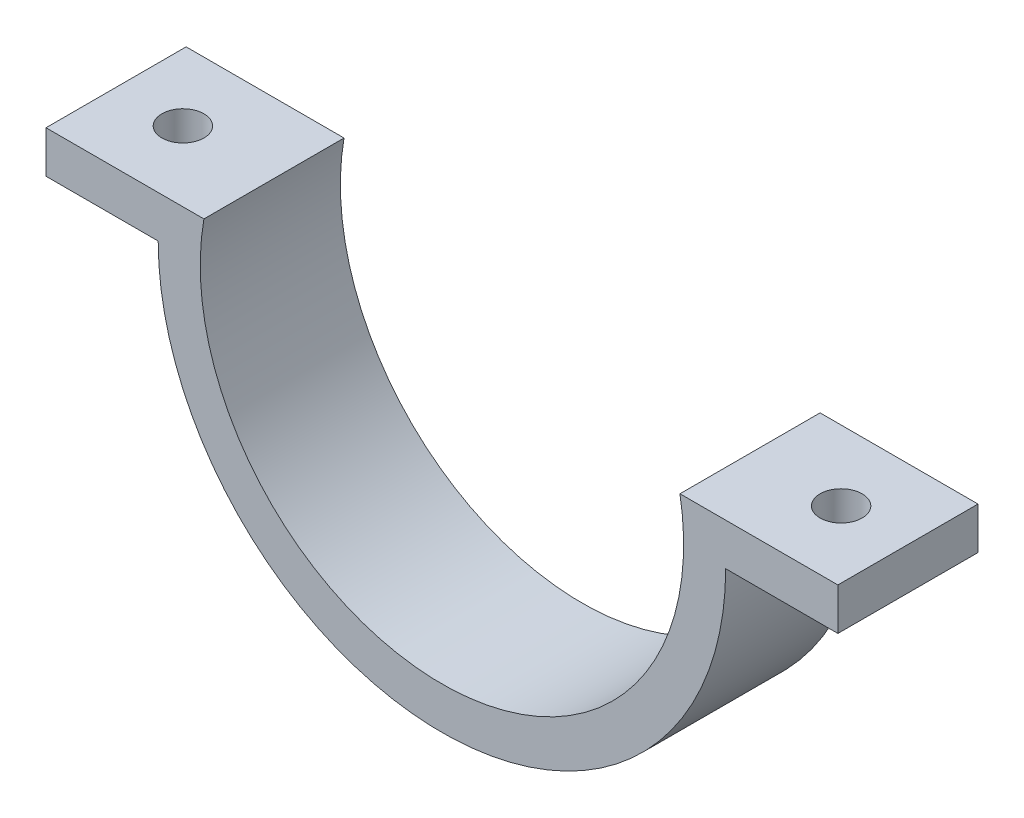
SolidWorks part; units mm, degrees
ref_plane "Front Plane" through (0, 0, 0) normal (0, 0, 1) x (1, 0, 0)
ref_plane "Top Plane" through (0, 0, 0) normal (0, 1, 0) x (1, 0, 0)
ref_plane "Right Plane" through (0, 0, 0) normal (1, 0, 0) x (0, 0, -1)
sketch "Sketch1" plane through (0, 0, 0) normal (0, 0, 1) x (1, 0, 0)
  line L0 (0, 0) -> (0, 3) construction
  line L1 (16.9871, 3) -> (-16.9871, 3) construction
  line L2 (-16.9871, 3) -> (-26.9871, 3)
  line L3 (16.9871, 3) -> (26.9871, 3)
  line L4 (-26.9871, 3) -> (-26.9871, 0)
  line L5 (-26.9871, 0) -> (-20.25, 0)
  line L6 (26.9871, 0) -> (20.25, 0)
  line L7 (26.9871, 3) -> (26.9871, 0)
  line L8 (-26.9871, 3) -> (-28.2571, 3)
  line L9 (-28.2571, 3) -> (-28.2571, 0)
  line L10 (-28.2571, 0) -> (-26.9871, 0)
  line L12 (26.9871, 3) -> (28.2571, 3)
  line L13 (26.9871, 3) -> (26.9871, 0)
  line L14 (26.9871, 0) -> (28.2571, 0)
  line L15 (28.2571, 3) -> (28.2571, 0)
  circle A0 centre (0, 0) radius 17.25
  arc A1 (-20.25, 0) -> (20.25, 0) centre (0, 0) ccw
  dimension "D1" = 34.5
  dimension "D4" = 3
  dimension "D2" = 3
  dimension "D3" = 10
  dimension "D5" = 3
  dimension "D6" = 1.27
  dimension "D7" = 1.27
extrude "Boss-Extrude1" add sketch "Sketch1" along normal blind 10 contours L5 A1 L6 L7 L3 A0 L2 L4 | L15 L12 L7 L14 | L9 L10 L4 L8
sketch "Sketch2" plane through (0, 3, 0) normal (0, 1, 0) x (1, 0, 0)
  line L0 (-26.9871, -5) -> (-24.9871, -5)
  line L2 (-24.9871, -5) -> (-16.9871, -5)
  line L3 (-16.9871, -10) -> (-16.9871, 0) construction
  line L5 (-26.9871, -5) -> (-26.9871, 0)
  line L6 (-16.9871, 0) -> (-28.2571, 0) construction
  line L7 (-28.2571, -10) -> (-28.2571, 0) construction
  circle A0 centre (-23.4871, -5) radius 1.5
  point P9 (-21.9871, -5)
  dimension "D2" = 3
  dimension "D1" = 2
  dimension "D3" = 1.27
extrude "Cut-Extrude1" cut sketch "Sketch2" against normal up to surface (3 mm away) contours L2 A0 | L2 A0 up to face at (-24.2536, 0, 5)
mirror "Mirror1" about plane through (0, 0, 0) normal (1, 0, 0) of "Cut-Extrude1"
